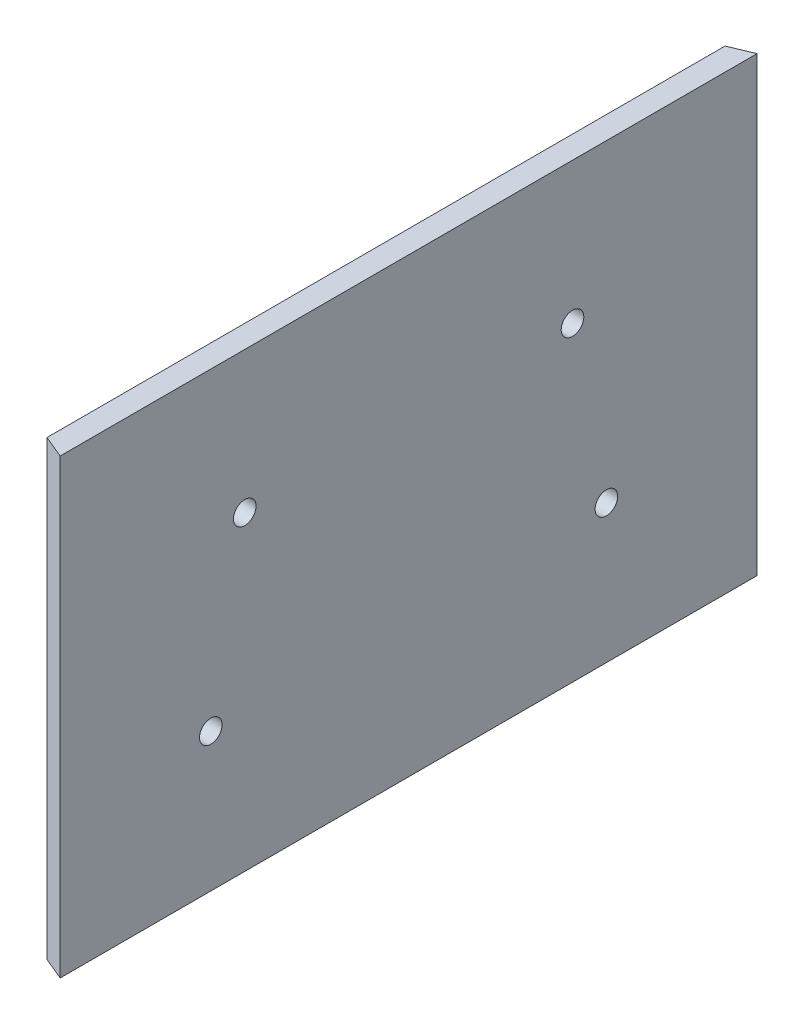
SolidWorks part; units mm, degrees
material "6061 合金"
ref_plane "前视基准面" through (0, 0, 0) normal (0, 0, 1) x (1, 0, 0)
ref_plane "上视基准面" through (0, 0, 0) normal (0, 1, 0) x (1, 0, 0)
ref_plane "右视基准面" through (0, 0, 0) normal (1, 0, 0) x (0, 0, -1)
sketch "草图1" plane through (0, 0, 0) normal (0, 0, 1) x (1, 0, 0)
  line L1 (0, 50) -> (-4, 50)
  line L2 (0, 50) -> (0, -30)
  line L3 (0, -30) -> (-4, -30)
  line L4 (-4, 50) -> (-4, -30)
  dimension "D1" = 4
  dimension "D2" = 80
extrude "拉伸3" add sketch "草图1" against normal blind 120
sketch "草图3" plane through (-4, 0, 0) normal (-1, 0, 0) x (0, 0, 1)
  line L0 (-60, 50) -> (-60, -32.9702) construction
  line L1 (-120, 50) -> (0, 50) construction
  line L2 (-89, 25) -> (-31, 25) construction
  line L3 (-95, -5.5) -> (-25, -5.5) construction
  circle A0 centre (-89, 25) radius 2
  circle A1 centre (-95, -5.5) radius 2
  circle A2 centre (-25, -5.5) radius 2
  circle A3 centre (-31, 25) radius 2
  dimension "D5" = 4
  dimension "D1" = 25
  dimension "D2" = 55.5
  dimension "D3" = 58
  dimension "D4" = 70
extrude "切除-拉伸1" cut sketch "草图3" against normal through all
sketch "草图4" plane through (0, 50, 0) normal (0, 1, 0) x (-1, 0, 0)
  line L0 (4, 0) -> (0, 1.6569)
  line L1 (0, 1.6569) -> (0, 0)
  line L2 (0, 0) -> (4, 0)
  line L3 (4, -120) -> (0, -120)
  line L4 (0, -120) -> (0, -121.6569)
  line L5 (0, -121.6569) -> (4, -120)
  dimension "D1" = 22.5
  dimension "D2" = 22.5
extrude "拉伸4" add sketch "草图4" against normal up to surface (80 mm away) up to face at (-2, -30, -60)
